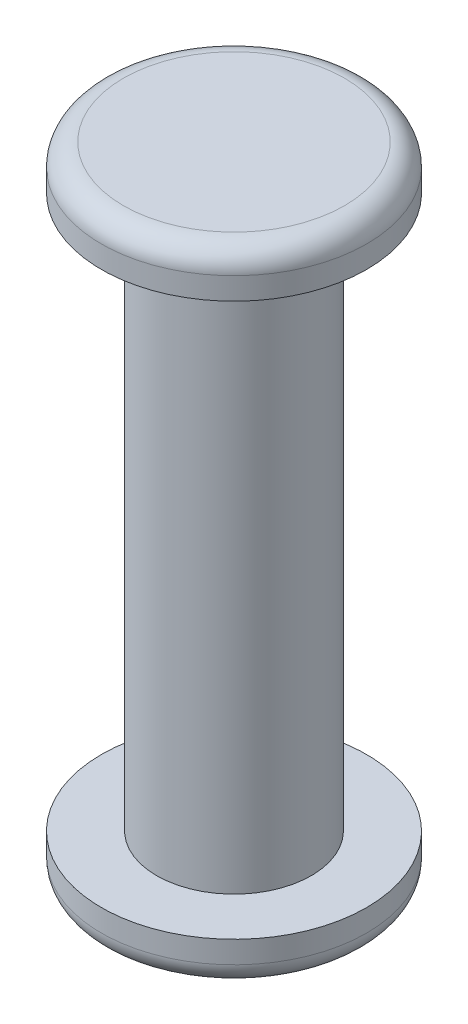
SolidWorks part; units mm, degrees
ref_plane "Front Plane" through (0, 0, 0) normal (0, 0, 1) x (1, 0, 0)
ref_plane "Top Plane" through (0, 0, 0) normal (0, 1, 0) x (1, 0, 0)
ref_plane "Right Plane" through (0, 0, 0) normal (1, 0, 0) x (0, 0, -1)
sketch "Sketch1" plane through (0, 0, 0) normal (0, 1, 0) x (1, 0, 0)
  circle A0 centre (0, 0) radius 1.75
  dimension "D1" = 3.5
extrude "Boss-Extrude1" add sketch "Sketch1" along normal blind 12.5
sketch "Sketch2" plane through (0, 0, 0) normal (0, 0, 1) x (1, 0, 0)
  line L0 (0, 0) -> (0, 12.5) construction
  line L1 (-1.75, 0) -> (1.75, 0) construction
  line L2 (1.75, 12.5) -> (-1.75, 12.5) construction
  line L3 (-7.3525, 6.25) -> (7.3525, 6.25) construction
  line L4 (0, 12.5) -> (-3, 12.5)
  line L5 (-3, 12.5) -> (-3, 13.5)
  line L6 (-3, 13.5) -> (0, 13.5)
  line L7 (0, 13.5) -> (0, 12.5)
  line L8 (-3, -1) -> (0, -1)
  line L9 (-3, 0) -> (-3, -1)
  line L10 (0, 0) -> (-3, 0)
  line L11 (0, -1) -> (0, 0)
  point P9 (0, 6.25)
  dimension "D1" = 1
  dimension "D2" = 3
revolve "Revolve1" add sketch "Sketch2" angle 360 about L0
fillet "Fillet1" radius 0.5 2 edges at (3, -1, 0) (3, 13.5, 0)
